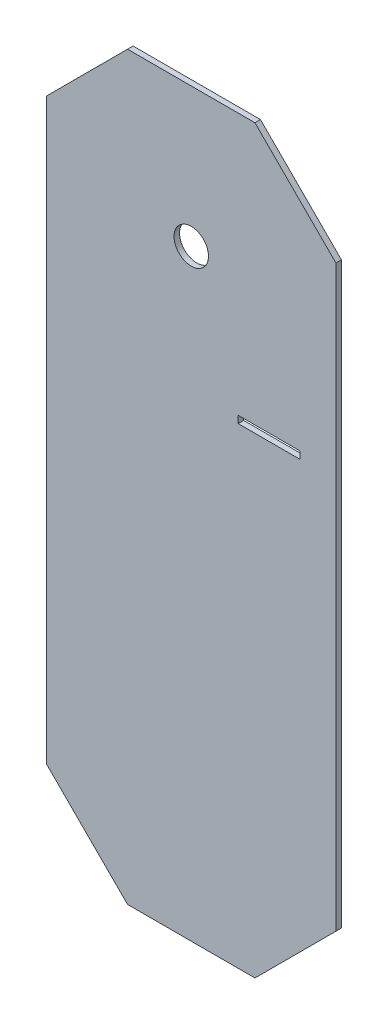
SolidWorks part; units mm, degrees
ref_plane "Спереди" through (0, 0, 0) normal (0, 0, 1) x (1, 0, 0)
ref_plane "Сверху" through (0, 0, 0) normal (0, 1, 0) x (1, 0, 0)
ref_plane "Справа" through (0, 0, 0) normal (1, 0, 0) x (0, 0, -1)
sketch "Эскиз1" plane through (0, 0, 0) normal (0, 0, 1) x (1, 0, 0)
  line L0 (-105, 539.9964) -> (-105, 203.9939)
  line L1 (105, 539.9964) -> (105, 203.9939)
  line L2 (0, 639.9964) -> (0, 656.3633) construction
  line L3 (46.2224, 640.7741) -> (-46.2224, 640.7741)
  line L4 (-105, 539.9964) -> (-105, 581.9964)
  line L5 (-105, 581.9964) -> (-46.2224, 640.7741)
  line L6 (105, 539.9964) -> (105, 581.9964)
  line L7 (105, 581.9964) -> (46.2224, 640.7741)
  line L8 (-100, 371.9952) -> (-247.0361, 371.9952) construction
  line L9 (105, 203.9939) -> (105, 161.9939)
  line L10 (105, 161.9939) -> (46.2224, 103.2162)
  line L11 (46.2224, 103.2162) -> (-46.2224, 103.2162)
  line L12 (-105, 161.9939) -> (-46.2224, 103.2162)
  line L13 (-105, 203.9939) -> (-105, 161.9939)
  circle A3 centre (0, 539.9964) radius 12.5
extrude "Вытянуть1" add sketch "Эскиз1" along normal blind 4
sketch "Эскиз2" plane through (0, 0, 4) normal (0, 0, 1) x (1, 0, 0)
  line L5 (34.0313, 445.574) -> (79.0313, 445.574)
  line L6 (34.0313, 445.574) -> (34.0313, 450.824)
  line L7 (34.0313, 450.824) -> (79.0313, 450.824)
  line L8 (79.0313, 445.574) -> (79.0313, 450.824)
extrude "Вырез-Вытянуть1" cut sketch "Эскиз2" against normal through all
